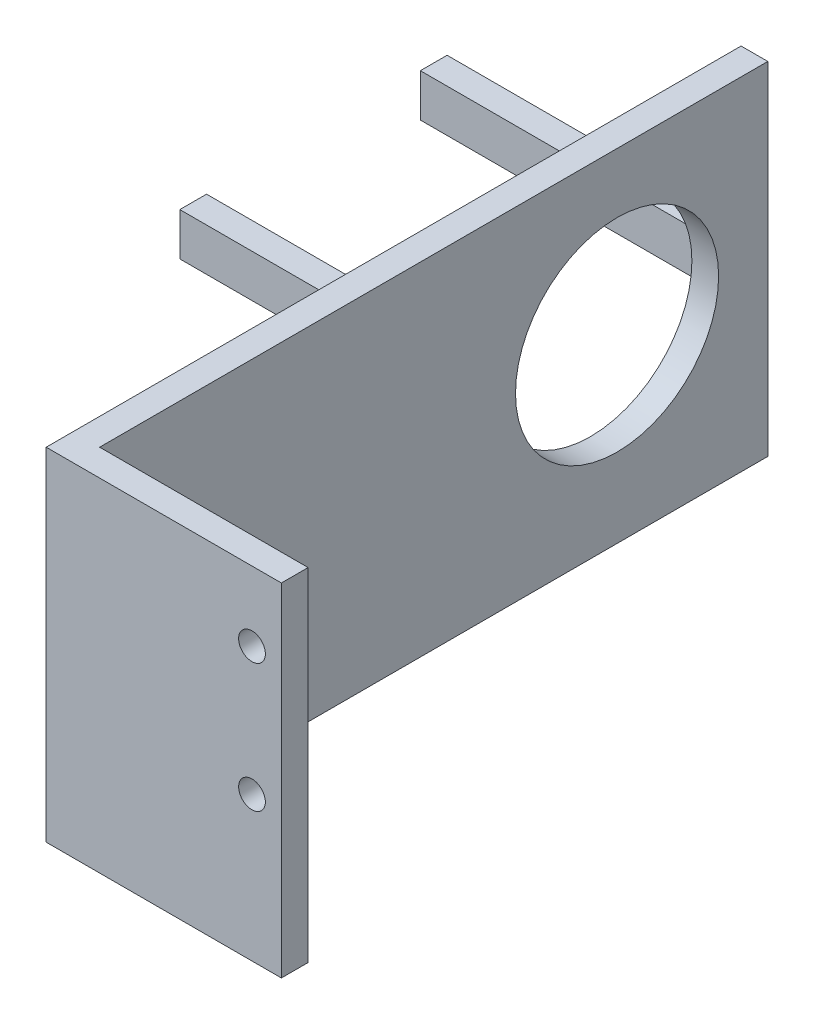
SolidWorks part; units mm, degrees
ref_plane "Plan de face" through (0, 0, 0) normal (0, 0, 1) x (1, 0, 0)
ref_plane "Plan de dessus" through (0, 0, 0) normal (0, 1, 0) x (1, 0, 0)
ref_plane "Plan de droite" through (0, 0, 0) normal (1, 0, 0) x (0, 0, -1)
sketch "Esquisse1" plane through (0, 0, 0) normal (0, 0, 1) x (1, 0, 0)
  line L1 (0, 0) -> (-39, 0)
  line L2 (0, 0) -> (0, 64)
  line L3 (0, 64) -> (-39, 64)
  line L4 (-39, 0) -> (-39, 64)
  circle A0 centre (-5.5, 51) radius 2.5
  circle A1 centre (-5.5, 27) radius 2.5
  point P9 (0, 0)
  dimension "D3" = 5
  dimension "D1" = 64
  dimension "D2" = 39
  dimension "D4" = 5.5
  dimension "D5" = 24
  dimension "D6" = 13
extrude "Boss.-Extru.1" add sketch "Esquisse1" along normal blind 5
sketch "Esquisse2" plane through (0, 0, 5) normal (0, 0, 1) x (1, 0, 0)
  line L0 (-39, 0) -> (0, 0) construction
  line L1 (-39, 64) -> (-44, 64)
  line L2 (-39, 64) -> (-39, 0)
  line L3 (-39, 0) -> (-44, 0)
  line L4 (-44, 64) -> (-44, 0)
  dimension "D1" = 5
extrude "Boss.-Extru.2" add sketch "Esquisse2" against normal blind 130
sketch "Esquisse3" plane through (-44, 0, 0) normal (-1, 0, 0) x (0, 0, 1)
  line L0 (-125, 64) -> (5, 64) construction
  line L1 (-125, 64) -> (-125, 0) construction
  circle A0 centre (-96.8, 33.8) radius 19
  dimension "D1" = 38
  dimension "D3" = 28.2
  dimension "D2" = 30.2
extrude "Enlèv. mat.-Extru.1" cut sketch "Esquisse3" against normal through all
sketch "Esquisse4" plane through (-44, 0, 0) normal (-1, 0, 0) x (0, 0, 1)
  line L1 (-72, 38) -> (-77, 38)
  line L2 (-72, 38) -> (-72, 30)
  line L3 (-72, 30) -> (-77, 30)
  line L4 (-77, 38) -> (-77, 30)
  line L5 (-82.2362, 34) -> (5, 34) construction
  line L6 (5, 64) -> (5, 0) construction
  line L7 (-125, 64) -> (5, 64) construction
  line L8 (-125, 64) -> (-125, 0) construction
  line L9 (-97, 34) -> (-97, 62.8026) construction
  line L10 (-122, 30) -> (-117, 30)
  line L11 (-122, 38) -> (-122, 30)
  line L12 (-122, 38) -> (-117, 38)
  line L13 (-117, 38) -> (-117, 30)
  point P10 (-97, 34)
  point P11 (0, 0)
  dimension "D1" = 5
  dimension "D2" = 8
  dimension "D3" = 30
  dimension "D4" = 4
  dimension "D5" = 48
extrude "Boss.-Extru.3" add sketch "Esquisse4" along normal blind 52
